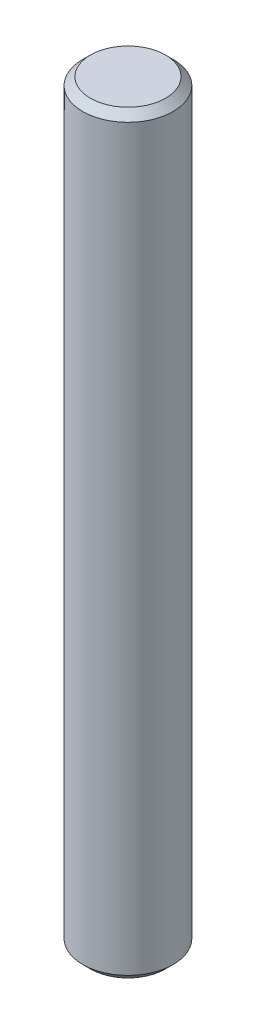
SolidWorks part; units mm, degrees
ref_plane "Front Plane" through (0, 0, 0) normal (0, 0, 1) x (1, 0, 0)
ref_plane "Top Plane" through (0, 0, 0) normal (0, 1, 0) x (1, 0, 0)
ref_plane "Right Plane" through (0, 0, 0) normal (1, 0, 0) x (0, 0, -1)
ref_plane "Plane1" through (0, 0, 0) normal (0, 0, -1) x (-1, 0, 0)
sketch "Sketch1" plane through (0, 0, 0) normal (0, 0, -1) x (-1, 0, 0)
  line L0 (-2.4882, 0) -> (0, 0)
  line L1 (0, 0) -> (0, 50)
  line L2 (0, 50) -> (-2.4882, 50)
  line L3 (-2.4882, 50) -> (-2.9962, 49.492)
  line L4 (-2.9962, 49.492) -> (-2.9962, 0.508)
  line L5 (-2.9962, 0.508) -> (-2.4882, 0)
  line L6 (0, 0) -> (0, 50) construction
revolve "Revolve1" add sketch "Sketch1" angle 360 about L6
